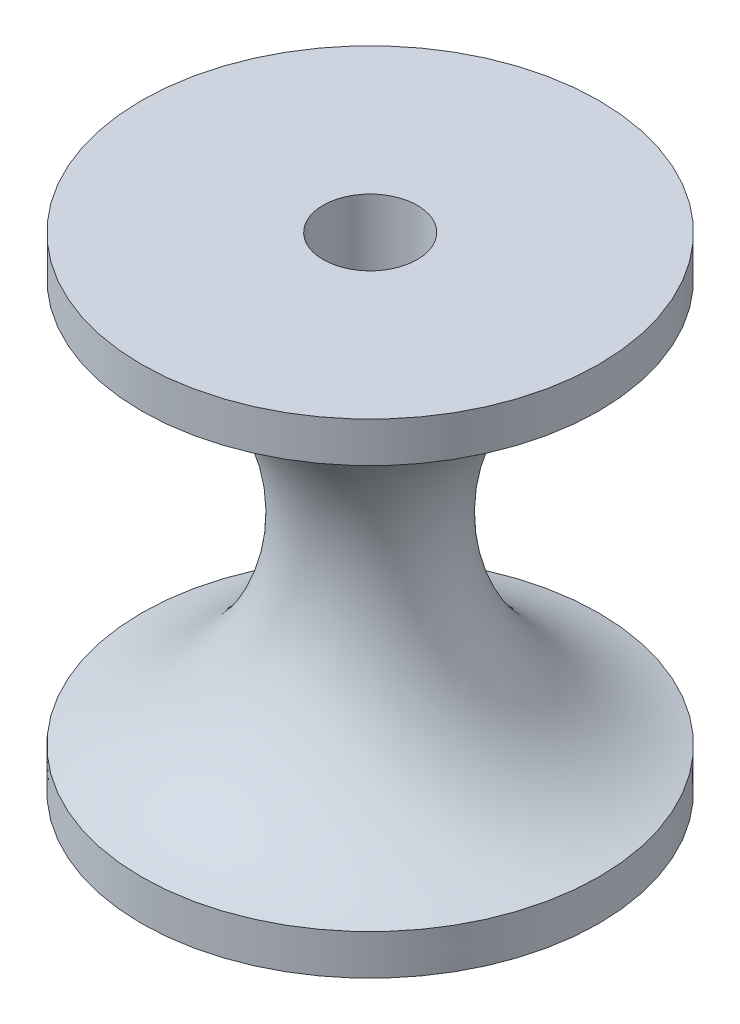
SolidWorks part; units mm, degrees
ref_plane "Front Plane" through (0, 0, 0) normal (0, 0, 1) x (1, 0, 0)
ref_plane "Top Plane" through (0, 0, 0) normal (0, 1, 0) x (1, 0, 0)
ref_plane "Right Plane" through (0, 0, 0) normal (1, 0, 0) x (0, 0, -1)
sketch "Sketch1" plane through (0, 0, 0) normal (0, 0, 1) x (1, 0, 0)
  line L0 (0, 0) -> (0, 36)
  line L1 (0, 36) -> (-17, 36)
  line L2 (0, 0) -> (-17, 0)
  line L3 (-17, 33) -> (-17, 36)
  line L4 (-17.0001, 3) -> (-17, 0)
  arc A0 (-17, 33) -> (-17.0001, 3) centre (-21, 18) cw
  point P6 (-17, 3)
  point P7 (-21, 18)
  point P9 (-17, 33)
  dimension "D1" = 36
  dimension "D2" = 17
  dimension "D3" = 17
  dimension "D4" = 3
revolve "Revolve1" add sketch "Sketch1" angle 360 about L0
sketch "Sketch3" plane through (0, 36, 0) normal (0, 1, 0) x (1, 0, 0)
  circle A0 centre (0, 0) radius 3.5
  dimension "D1" = 7
extrude "Cut-Extrude1" cut sketch "Sketch3" against normal up to next
